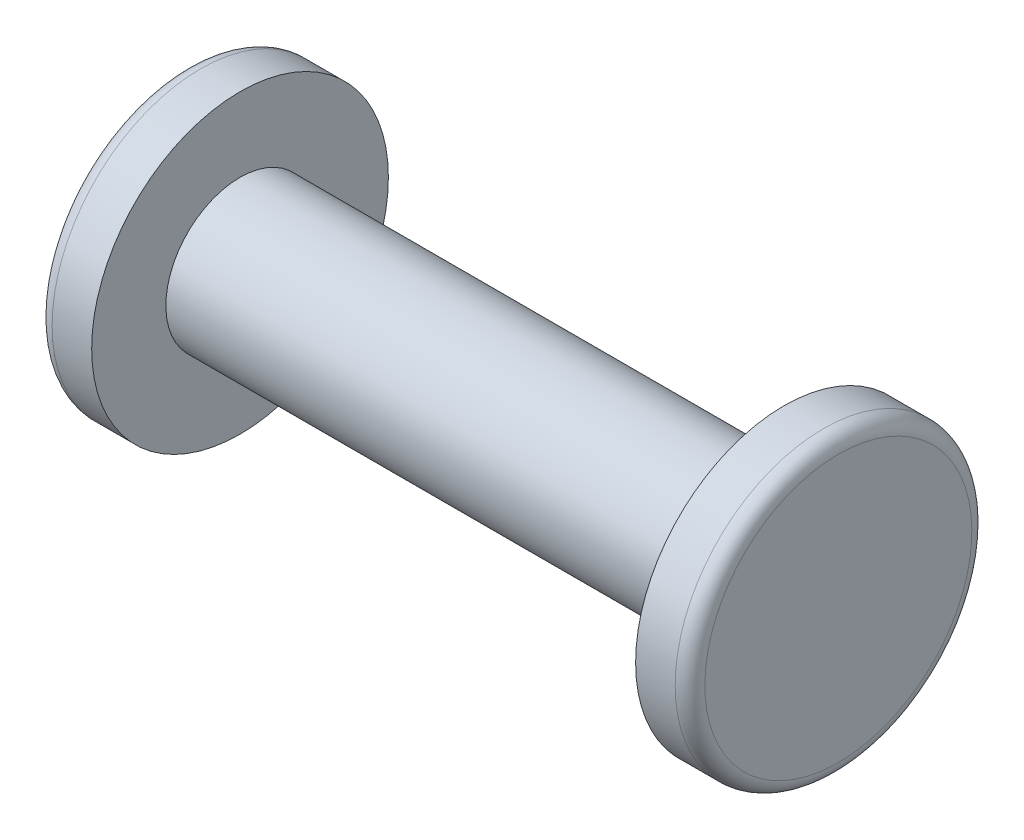
SolidWorks part; units mm, degrees
material "AISI 304"
ref_plane "前视基准面" through (0, 0, 0) normal (0, 0, 1) x (1, 0, 0)
ref_plane "上视基准面" through (0, 0, 0) normal (0, 1, 0) x (1, 0, 0)
ref_plane "右视基准面" through (0, 0, 0) normal (1, 0, 0) x (0, 0, -1)
other "Configuration Table"
sketch "草图1" plane through (0, 0, 0) normal (0, 0, 1) x (1, 0, 0)
  line L0 (0, 0) -> (0, 2.7)
  line L1 (0.3, 3) -> (1.1, 3)
  line L2 (1.1, 3) -> (1.1, 1.5)
  line L3 (1.1, 1.5) -> (12.1, 1.5)
  line L4 (12.1, 1.5) -> (12.1, 3)
  line L5 (12.1, 3) -> (12.9, 3)
  line L6 (13.2, 2.7) -> (13.2, 0)
  line L7 (13.2, 0) -> (0, 0)
  arc A1 (12.9, 3) -> (13.2, 2.7) centre (12.9, 2.7) cw
  arc A2 (0, 2.7) -> (0.3, 3) centre (0.3, 2.7) cw
  point P12 (13.2, 3)
  point P15 (0, 3)
  dimension "D1" = 1.5
  dimension "D8" = 0.3
  dimension "D2" = 3
  dimension "D3" = 1.1
  dimension "D4" = 1.1
  dimension "D5" = 11
  dimension "D6" = 3
  dimension "D7" = 13.2
revolve "旋转1" add sketch "草图1" angle 360 about L7
